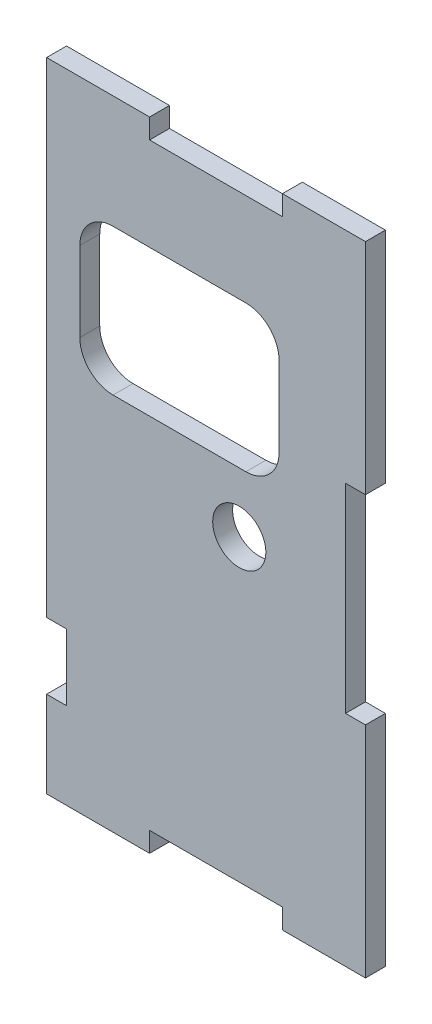
SolidWorks part; units mm, degrees
ref_plane "Front Plane" through (0, 0, 0) normal (0, 0, 1) x (1, 0, 0)
ref_plane "Top Plane" through (0, 0, 0) normal (0, 1, 0) x (1, 0, 0)
ref_plane "Right Plane" through (0, 0, 0) normal (1, 0, 0) x (0, 0, -1)
sketch "Sketch1" plane through (0, 0, 0) normal (0, 0, 1) x (1, 0, 0)
  line L0 (0, 0) -> (0, 96)
  line L1 (0, 96) -> (15.5, 96)
  line L2 (15.5, 96) -> (15.5, 93)
  line L3 (15.5, 93) -> (35.5, 93)
  line L4 (35.5, 93) -> (35.5, 96)
  line L5 (35.5, 96) -> (48, 96)
  line L6 (48, 96) -> (48, 0)
  line L7 (48, 0) -> (35.5, 0)
  line L8 (35.5, 0) -> (35.5, 3)
  line L9 (35.5, 3) -> (15.5, 3)
  line L10 (15.5, 3) -> (15.5, 0)
  line L11 (15.5, 0) -> (0, 0)
  dimension "D1" = 90
  dimension "D2" = 20
  dimension "D3" = 3
  dimension "D4" = 12.5
  dimension "D5" = 48
extrude "Boss-Extrude1" add sketch "Sketch1" along normal blind 3
sketch "Sketch2" plane through (0, 0, 3) normal (0, 0, 1) x (1, 0, 0)
  line L1 (3, 23) -> (0, 23)
  line L2 (3, 23) -> (3, 13)
  line L3 (3, 13) -> (0, 13)
  line L4 (0, 23) -> (0, 13)
  line L5 (15.5, 3) -> (35.5, 3) construction
  line L6 (0, 96) -> (0, 0) construction
  dimension "D1" = 10
  dimension "D2" = 3
  dimension "D3" = 10
extrude "Cut-Extrude1" cut sketch "Sketch2" against normal through all
sketch "Sketch3" plane through (0, 0, 0) normal (0, 0, -1) x (-1, 0, 0)
  line L0 (-35.5, 93) -> (-15.5, 93) construction
  line L1 (0, 96) -> (0, 23) construction
  circle A2 centre (-29, 48) radius 4
  dimension "D2" = 8
  dimension "D4" = 45
  dimension "D7" = 29
extrude "Cut-Extrude2" cut sketch "Sketch3" against normal through all
sketch "Sketch4" plane through (0, 0, 0) normal (0, 0, -1) x (-1, 0, 0)
  line L0 (-48, 0) -> (-48, 96) construction
  line L1 (-48, 63) -> (-45, 63)
  line L2 (-48, 63) -> (-48, 33)
  line L3 (-48, 33) -> (-45, 33)
  line L4 (-45, 63) -> (-45, 33)
  line L5 (-48, 96) -> (-35.5, 96) construction
  dimension "D1" = 3
  dimension "D2" = 30
  dimension "D3" = 33
extrude "Cut-Extrude3" cut sketch "Sketch4" against normal through all
sketch "Sketch5" plane through (0, 0, 0) normal (0, 0, -1) x (-1, 0, 0)
  line L0 (0, 96) -> (0, 23) construction
  line L1 (-10, 57) -> (-30, 57)
  line L2 (-5, 62) -> (-5, 74)
  line L3 (-10, 79) -> (-30, 79)
  line L4 (-35, 62) -> (-35, 74)
  line L5 (-35.5, 93) -> (-15.5, 93) construction
  arc A0 (-30, 57) -> (-35, 62) centre (-30, 62) cw
  arc A1 (-10, 57) -> (-5, 62) centre (-10, 62) ccw
  arc A2 (-5, 74) -> (-10, 79) centre (-10, 74) ccw
  arc A3 (-30, 79) -> (-35, 74) centre (-30, 74) ccw
  dimension "D1" = 5
  dimension "D2" = 20
  dimension "D3" = 12
  dimension "D4" = 5
  dimension "D5" = 14
extrude "Cut-Extrude4" cut sketch "Sketch5" against normal through all
